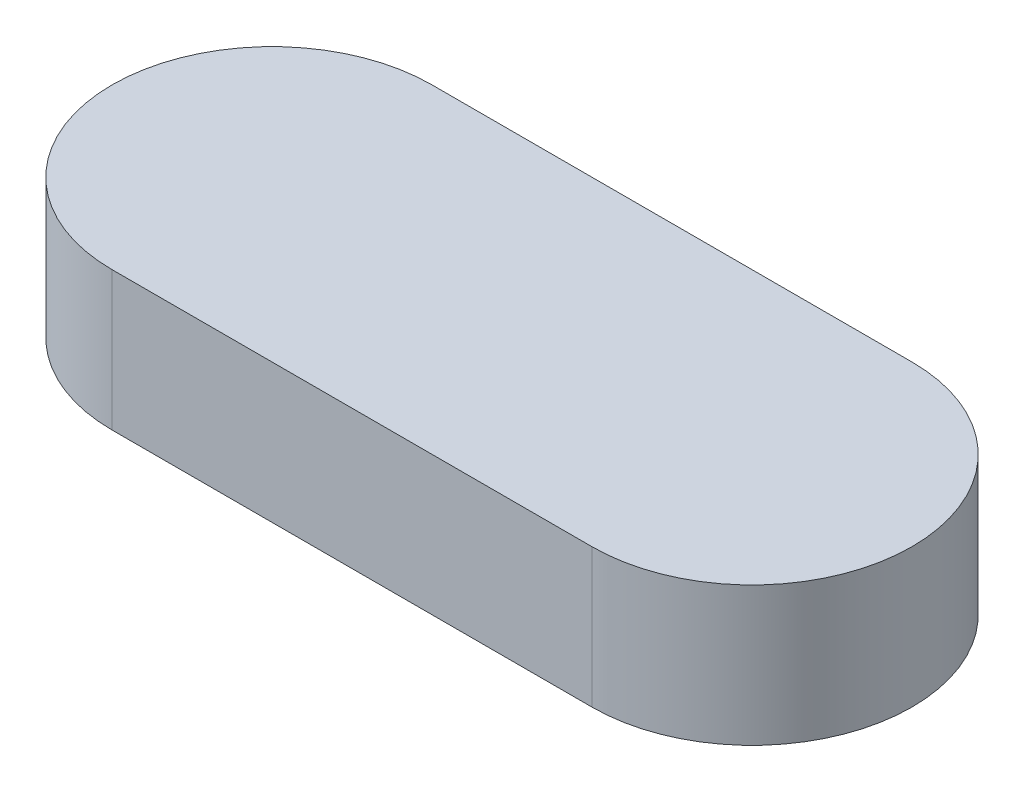
SolidWorks part; units mm, degrees
ref_plane "Front Plane" through (0, 0, 0) normal (0, 0, 1) x (1, 0, 0)
ref_plane "Top Plane" through (0, 0, 0) normal (0, 1, 0) x (1, 0, 0)
ref_plane "Right Plane" through (0, 0, 0) normal (1, 0, 0) x (0, 0, -1)
sketch "Sketch1" plane through (0, 0, 0) normal (0, 1, 0) x (1, 0, 0)
  line L0 (9, 0) -> (-9, 0) construction
  line L11 (9, -6) -> (-9, -6)
  line L12 (9, 6) -> (-9, 6)
  arc A0 (9, -6) -> (9, 6) centre (9, 0) ccw
  arc A1 (-9, 6) -> (-9, -6) centre (-9, 0) ccw
  point P2 (0, 0)
  dimension "D1" = 30
  dimension "D2" = 12
extrude "Boss-Extrude1" add sketch "Sketch1" along normal blind 5.21
